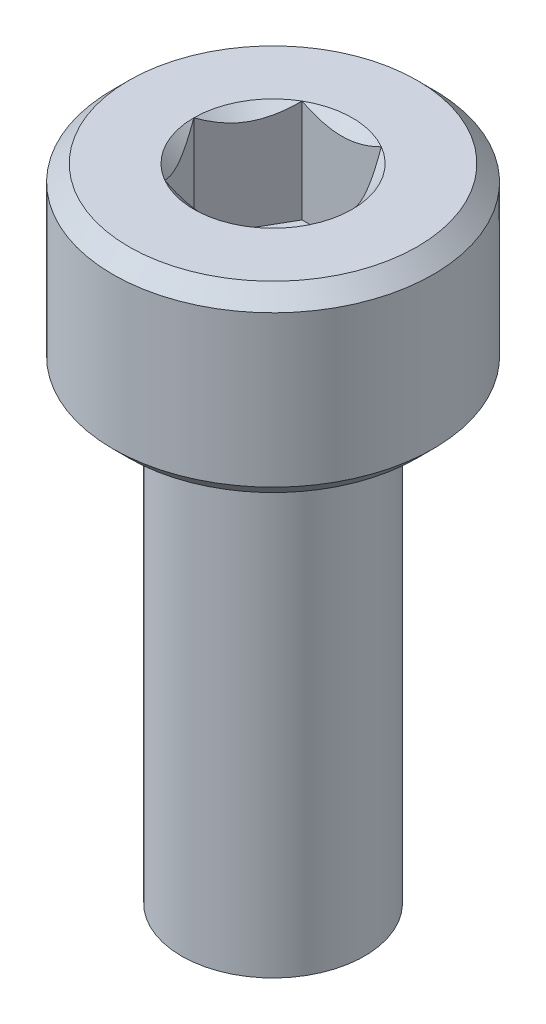
SolidWorks part; units mm, degrees
ref_plane "Front" through (0, 0, 0) normal (0, 0, 1) x (1, 0, 0)
ref_plane "Top" through (0, 0, 0) normal (0, 1, 0) x (1, 0, 0)
ref_plane "Right" through (0, 0, 0) normal (1, 0, 0) x (0, 0, -1)
sketch "Sketch1" plane through (0, 0, 0) normal (0, 1, 0) x (1, 0, 0)
  circle A0 centre (0, 0) radius 3.5
  dimension "D1" = 7
extrude "Boss-Extrude1" add sketch "Sketch1" along normal blind 4
sketch "Sketch2" plane through (0, 4, 0) normal (0, 1, 0) x (1, 0, 0)
  line L1 (0.866, 1.5) -> (-0.866, 1.5)
  line L2 (-0.866, 1.5) -> (-1.7321, 0)
  line L3 (-1.7321, 0) -> (-0.866, -1.5)
  line L4 (-0.866, -1.5) -> (0.866, -1.5)
  line L5 (0.866, -1.5) -> (1.7321, 0)
  line L6 (1.7321, 0) -> (0.866, 1.5)
  circle A0 centre (0, 0) radius 1.5 construction
  point P10 (0, 1.5)
  dimension "D1" = 3
extrude "Cut-Extrude1" cut sketch "Sketch2" against normal blind 2.25
sketch "Sketch3" plane through (0, 4, 0) normal (0, 1, 0) x (1, 0, 0)
  circle A0 centre (0, 0) radius 1.7321
extrude "Cut-Extrude2" cut sketch "Sketch3" against normal through all draft 45
chamfer "Chamfer1" distance 0.35 angle 45 2 edges at (0, 0, 3.5) (0, 4, 3.5)
sketch "草图1" plane through (0, 0, 0) normal (0, -1, 0) x (-1, 0, 0)
  circle A0 centre (0, 0) radius 2
  dimension "D1" = 4
extrude "凸台-拉伸1" add sketch "草图1" along normal blind 10
